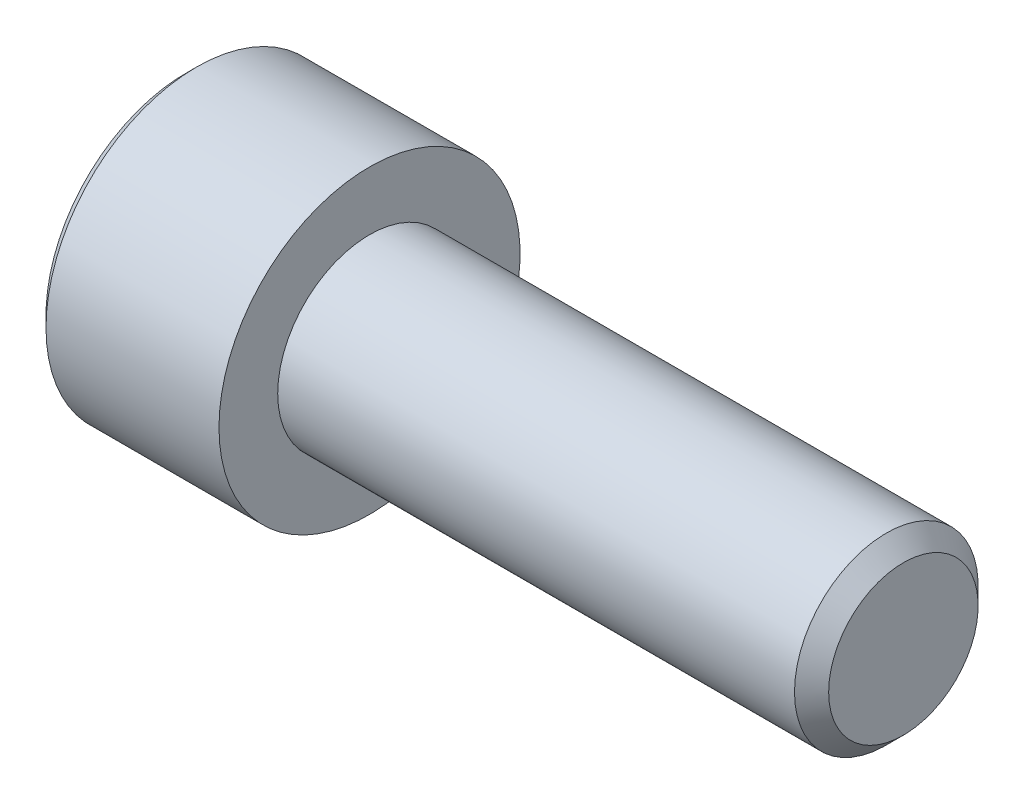
SolidWorks part; units mm, degrees
material "AISI Type A2 Tool Steel"
ref_plane "Front Plane" through (0, 0, 0) normal (0, 0, 1) x (1, 0, 0)
ref_plane "Top Plane" through (0, 0, 0) normal (0, 1, 0) x (1, 0, 0)
ref_plane "Right Plane" through (0, 0, 0) normal (1, 0, 0) x (0, 0, -1)
sketch "Sketch1" plane through (0, 0, 0) normal (0, 0, 1) x (1, 0, 0)
  line L0 (-2.1844, 0) -> (6.35, 0)
  line L1 (6.35, 0) -> (6.35, 1.0922)
  line L2 (6.35, 1.0922) -> (0, 1.0922)
  line L3 (0, 1.0922) -> (0, 1.7907)
  line L4 (0, 1.7907) -> (-2.1844, 1.7907)
  line L5 (-2.1844, 0) -> (-2.0451, 0) construction
  line L6 (-2.1844, 0) -> (-2.1844, 1.7907)
  dimension "D1" = 2.1844
  dimension "D2" = 6.35
  dimension "D3" = 3.5814
  dimension "D4" = 2.1844
revolve "Revolve1" add sketch "Sketch1" angle 360 about L5
chamfer "Chamfer1" distance 0.2032 angle 45 1 edges at (6.35, 0, 1.0922)
chamfer "Chamfer2" distance 0.127 angle 45 1 edges at (-2.1844, 0, 1.7907)
sketch "Sketch2" plane through (-2.1844, 0, 0) normal (-1, 0, 0) x (0, 0, 1)
  line L1 (1.1002, 0.1782) -> (0.3958, 1.0419)
  line L2 (0.3958, 1.0419) -> (-0.7044, 0.8637)
  line L3 (-0.7044, 0.8637) -> (-1.1002, -0.1782)
  line L4 (-1.1002, -0.1782) -> (-0.3958, -1.0419)
  line L5 (-0.3958, -1.0419) -> (0.7044, -0.8637)
  line L6 (0.7044, -0.8637) -> (1.1002, 0.1782)
  circle A0 centre (0, 0) radius 0.9652 construction
  dimension "D1" = 1.9304
extrude "Cut-Extrude1" cut sketch "Sketch2" against normal offset from surface (1.5494 mm away) 0.635 up to face at (0, 0, 1.7907)
